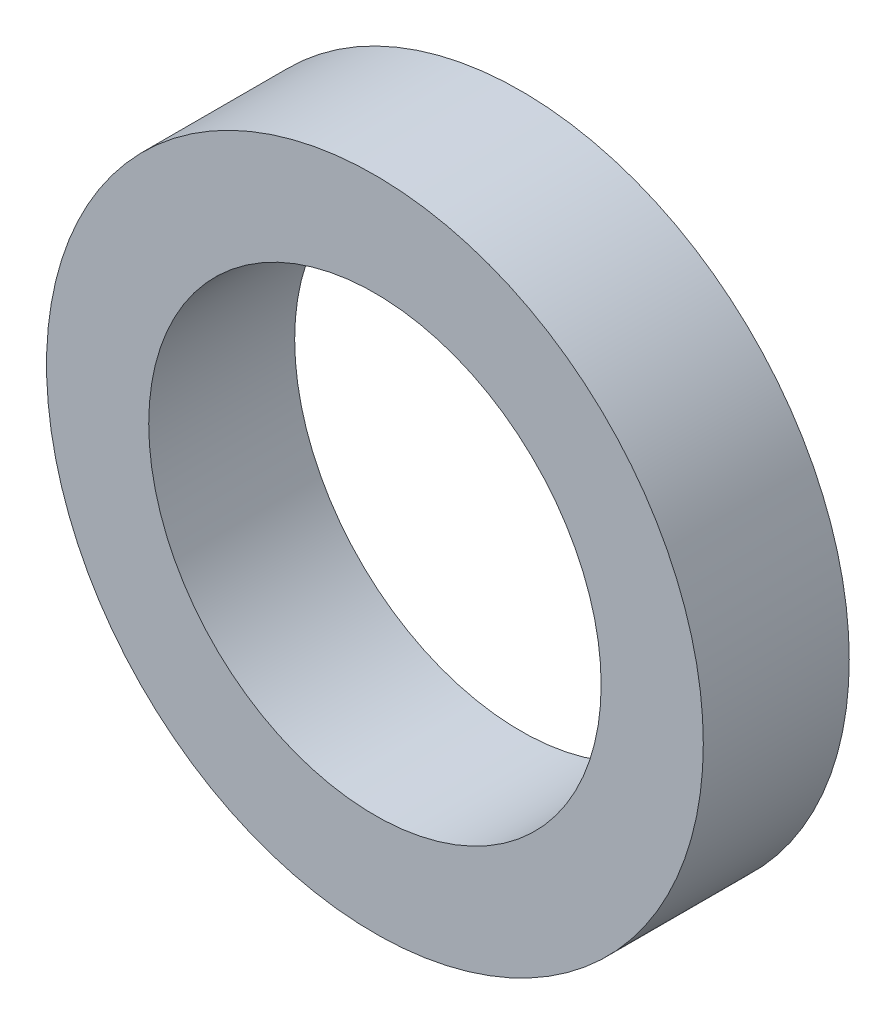
SolidWorks part; units mm, degrees
material "Медь"
ref_plane "Спереди" through (0, 0, 0) normal (0, 0, 1) x (1, 0, 0)
ref_plane "Сверху" through (0, 0, 0) normal (0, 1, 0) x (1, 0, 0)
ref_plane "Справа" through (0, 0, 0) normal (1, 0, 0) x (0, 0, -1)
other "Configuration Table"
sketch "Эскиз1" plane through (0, 0, 0) normal (0, 0, 1) x (1, 0, 0)
  circle A0 centre (0, 0) radius 3.1
  circle A1 centre (0, 0) radius 4.5
  dimension "D1" = 6.2
  dimension "D2" = 9
extrude "Бобышка-Вытянуть1" add sketch "Эскиз1" along normal blind 2
